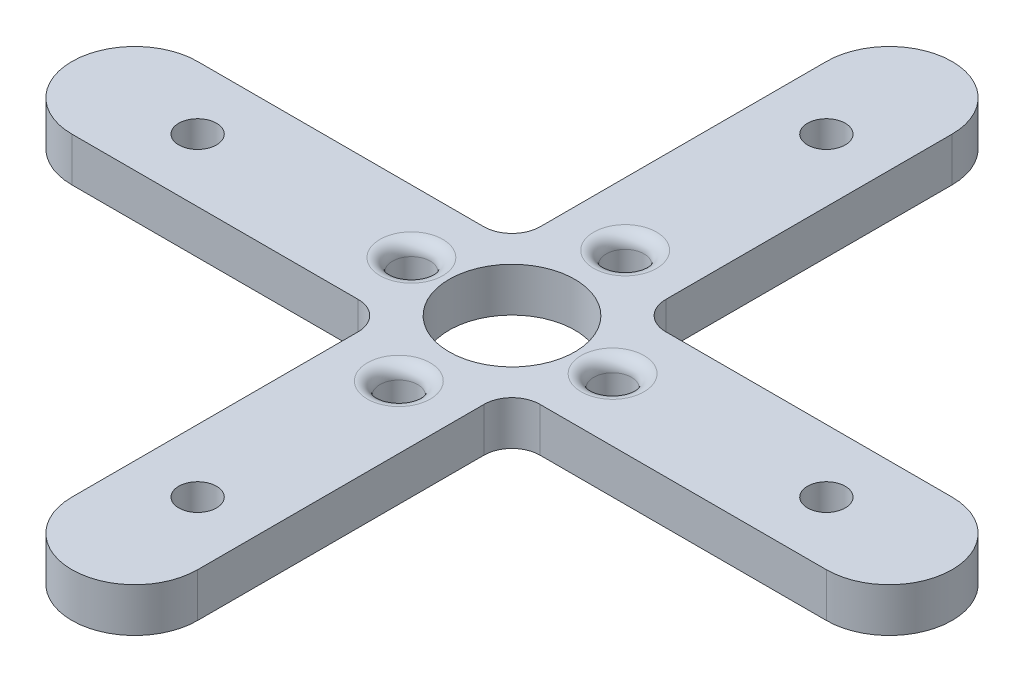
SolidWorks part; units mm, degrees
ref_plane "Alzado" through (0, 0, 0) normal (0, 0, 1) x (1, 0, 0)
ref_plane "Planta" through (0, 0, 0) normal (0, 1, 0) x (1, 0, 0)
ref_plane "Vista lateral" through (0, 0, 0) normal (1, 0, 0) x (0, 0, -1)
sketch "Croquis1" plane through (0, 0, 0) normal (0, 1, 0) x (1, 0, 0)
  line L0 (1.4757, 3.6958) -> (1.4757, 11.4846)
  line L6 (11.4757, 26.4535) -> (11.4757, 3.6555)
  line L7 (13.6977, 1.4535) -> (36.4757, 1.4535)
  line L15 (-23.5243, 1.4535) -> (-0.7665, 1.4535)
  line L16 (1.4757, -10.7887) -> (1.4757, -18.5775)
  line L17 (6.4757, -3.5465) -> (6.4757, 5.4535) construction
  line L18 (1.4757, -10.7887) -> (1.4757, -33.5465)
  line L19 (13.6977, -8.5465) -> (36.4757, -8.5465)
  line L20 (1.4757, 3.6958) -> (1.4757, 26.4535)
  line L21 (11.4757, -33.5465) -> (11.4757, -10.7484)
  line L22 (1.4757, -8.5775) -> (1.4757, -8.5465)
  line L23 (11.4757, -10.7484) -> (11.4757, -10.7887)
  line L24 (1.4757, -8.5465) -> (1.4757, -8.5775)
  line L25 (-23.5243, -8.5465) -> (-0.7665, -8.5465)
  line L26 (6.4757, -3.5465) -> (11.4757, -3.5465) construction
  line L29 (-17.0243, -3.5465) -> (-18.5243, -3.5465) construction
  line L30 (-0.0243, -3.5465) -> (-3.0243, -3.5465) construction
  line L31 (12.9757, -3.5465) -> (15.9757, -3.5465) construction
  circle A1 centre (6.4757, -3.5465) radius 5
  arc A2 (-0.7665, 1.4535) -> (1.4757, 3.6958) centre (-0.7665, 3.6958) ccw
  arc A4 (11.4757, -10.7484) -> (11.4757, -10.7887) centre (13.6977, -10.7685) ccw
  arc A5 (11.4757, 3.6958) -> (13.6977, 1.4535) centre (13.6977, 3.6756) ccw
  arc A6 (-23.5243, 1.4535) -> (-23.5243, -8.5465) centre (-23.5243, -3.5465) ccw
  arc A7 (36.4757, -8.5465) -> (36.4757, 1.4535) centre (36.4757, -3.5465) ccw
  arc A9 (11.4757, 26.4535) -> (1.4757, 26.4535) centre (6.4757, 26.4535) ccw
  arc A10 (11.4757, -10.7887) -> (13.6977, -8.5465) centre (13.6977, -10.7685) cw
  arc A11 (-0.7665, -8.5465) -> (1.4757, -10.7887) centre (-0.7665, -10.7887) cw
  arc A12 (1.4757, -33.5465) -> (11.4757, -33.5465) centre (6.4757, -33.5465) ccw
  circle A13 centre (-1.5243, -3.5465) radius 1.5
  circle A14 centre (14.4757, -3.5465) radius 1.5
  circle A15 centre (-18.5243, -3.5465) radius 1.5
  circle A16 centre (6.4757, 21.4535) radius 1.5
  circle A17 centre (31.4757, -3.5465) radius 1.5
  circle A18 centre (6.4757, -28.5465) radius 1.5
  circle A19 centre (6.4757, -12.5465) radius 1.5
  circle A20 centre (6.4757, 5.4535) radius 1.5
  point P0 (0, 0)
  dimension "D11" = 10
  dimension "D5" = 3
  dimension "D6" = 3
  dimension "D8" = 3
  dimension "D13" = 3
  dimension "D14" = 3
  dimension "D15" = 3
  dimension "D17" = 3
  dimension "D19" = 3
  dimension "D2" = 8
  dimension "D3" = 10
  dimension "D4" = 8
  dimension "D7" = 25
  dimension "D9" = 25
  dimension "D10" = 25
  dimension "D12" = 25
  dimension "D16" = 9
  dimension "D18" = 9
extrude "Saliente-Extruir2" add sketch "Croquis1" along normal blind 3.5
fillet "Redondeo9" radius 1 1 edges at (6.4757, 3.5, -3.9535)
fillet "Redondeo10" radius 1 1 edges at (14.4757, 3.5, 5.0465)
fillet "Redondeo11" radius 1 1 edges at (6.4757, 3.5, 14.0465)
fillet "Redondeo12" radius 1 1 edges at (-1.5243, 3.5, 5.0465)
